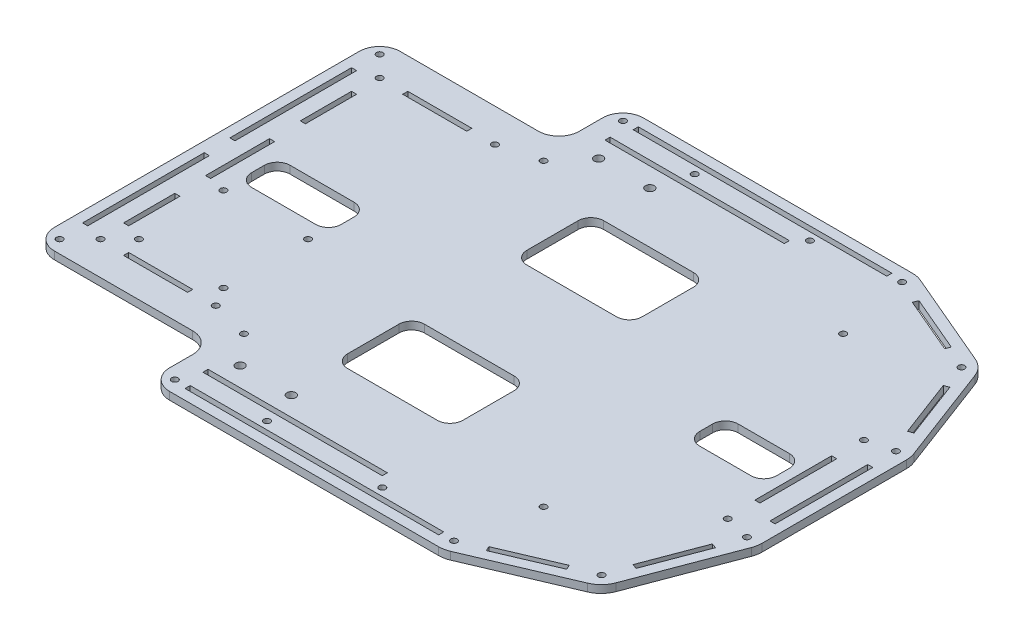
SolidWorks part; units mm, degrees
ref_plane "Piano frontale" through (0, 0, 0) normal (0, 0, 1) x (1, 0, 0)
ref_plane "Piano superiore" through (0, 0, 0) normal (0, 1, 0) x (1, 0, 0)
ref_plane "Piano destro" through (0, 0, 0) normal (1, 0, 0) x (0, 0, -1)
sketch "Schizzo1" plane through (0, 0, 0) normal (0, 1, 0) x (1, 0, 0)
  line L0 (70, 67.5) -> (70, 92.5)
  line L1 (0, 67.5) -> (70, 67.5)
  line L2 (0, 67.5) -> (0, -67.5)
  line L3 (0, -67.5) -> (70, -67.5)
  line L4 (70, 67.5) -> (70, -67.5) construction
  line L5 (70, 92.5) -> (185.0521, 92.5)
  line L6 (245, 30) -> (245, -30)
  line L7 (185.0521, -92.5) -> (70, -92.5)
  line L8 (70, -92.5) -> (70, -67.5)
  line L9 (245, 0) -> (70, 0) construction
  line L10 (245, 30) -> (228.3534, 74.0331)
  line L11 (228.3534, 74.0331) -> (185.0521, 92.5)
  line L12 (245, -30) -> (228.3534, -74.0331)
  line L13 (228.3534, -74.0331) -> (185.0521, -92.5)
  arc A0 (245, 30) -> (185.0521, 92.5) centre (185.0521, 32.5) ccw construction
  arc A1 (185.0521, -92.5) -> (245, -30) centre (185.0521, -32.5) ccw construction
  dimension "D5" = 60
  dimension "D6" = 60
  dimension "D1" = 135
  dimension "D2" = 70
  dimension "D3" = 175
  dimension "D4" = 25
extrude "Estrusione-Estrusione1" add sketch "Schizzo1" along normal blind 3
hole_wizard "Foro filettato M3x0.5-1" positions "Schizzo9" profile "Schizzo8" tap size "M3x0.5" standard "Ansi Metric"
sketch "Schizzo9" plane through (0, 3, 0) normal (0, 1, 0) x (1, 0, 0)
  line L102 (5, -62.5) -> (75, -62.5)
  line L103 (5, 62.5) -> (5, -62.5)
  line L104 (75, 62.5) -> (5, 62.5)
  line L105 (75, 87.5) -> (75, 62.5)
  line L106 (75, -62.5) -> (75, -87.5)
  line L107 (75, -87.5) -> (184.0304, -87.5)
  line L108 (184.0304, -87.5) -> (224.4305, -70.2704)
  line L109 (224.4305, -70.2704) -> (240, -29.0864)
  line L110 (240, -29.0864) -> (240, 29.0864)
  line L111 (240, 29.0864) -> (224.4305, 70.2704)
  line L112 (224.4305, 70.2704) -> (184.0304, 87.5)
  line L113 (184.0304, 87.5) -> (75, 87.5)
  line L114 (5, -62.5) -> (75, -62.5) construction
  line L115 (5, 62.5) -> (5, -62.5) construction
  line L116 (75, 62.5) -> (5, 62.5) construction
  line L117 (75, 87.5) -> (75, 62.5) construction
  line L118 (75, -62.5) -> (75, -87.5) construction
  line L119 (75, -87.5) -> (184.0304, -87.5) construction
  line L120 (184.0304, -87.5) -> (224.4305, -70.2704) construction
  line L121 (224.4305, -70.2704) -> (240, -29.0864) construction
  line L122 (240, -29.0864) -> (240, 29.0864) construction
  line L123 (240, 29.0864) -> (224.4305, 70.2704) construction
  line L124 (224.4305, 70.2704) -> (184.0304, 87.5) construction
  line L125 (184.0304, 87.5) -> (75, 87.5) construction
  point P0 (224.4305, 70.2704)
  point P2 (240, 29.0864)
  point P4 (240, -29.0864)
  point P6 (224.4305, -70.2704)
  point P8 (184.0304, -87.5)
  point P10 (184.0304, 87.5)
  point P12 (75, 87.5)
  point P14 (75, -87.5)
  point P16 (5, -62.5)
  point P18 (5, 62.5)
  dimension "D1" = 5
sketch "Schizzo8" plane through (224.4305, 3, -70.2704) normal (1, 0, 0) x (0, 0, 1)
  line L0 (0, 0) -> (0, 8.2511)
  line L1 (0, 8.2511) -> (1.25, 7.5)
  line L2 (1.25, 7.5) -> (1.25, 0)
  line L5 (1.25, 0) -> (0, 0)
  line L10 (0, 8.2511) -> (-1.25, 7.5) construction
  line L11 (0, -6.35) -> (0, 107.95) construction
  dimension "Tap Drill Dia." = 2.5
  dimension "Tap Drill Depth" = 7.5
  dimension "Drill Angle" = 118
cosmetic thread "Filettatura del foro1" parameters "D1"=5, "D2"=3
cosmetic thread "Filettatura del foro2" parameters "D1"=5, "D2"=3
cosmetic thread "Filettatura del foro3" parameters "D1"=5, "D2"=3
cosmetic thread "Filettatura del foro4" parameters "D1"=5, "D2"=3
cosmetic thread "Filettatura del foro5" parameters "D1"=5, "D2"=3
cosmetic thread "Filettatura del foro6" parameters "D1"=5, "D2"=3
cosmetic thread "Filettatura del foro7" parameters "D1"=5, "D2"=3
cosmetic thread "Filettatura del foro8" parameters "D1"=5, "D2"=3
cosmetic thread "Filettatura del foro9" parameters "D1"=5, "D2"=3
cosmetic thread "Filettatura del foro10" parameters "D1"=5, "D2"=3
sketch "Schizzo26" plane through (0, 3, 0) normal (0, 1, 0) x (1, 0, 0)
  line L0 (0, -67.5) -> (70, -67.5) construction
  line L1 (20, -67.5) -> (50, -67.5)
  line L2 (20, -67.5) -> (20, -64.5)
  line L3 (20, -64.5) -> (50, -64.5)
  line L4 (50, -67.5) -> (50, -64.5)
  line L6 (50, -66) -> (70, -66) construction
  line L7 (70, -66) -> (70, -67.5) construction
  line L8 (20, -66) -> (0, -66) construction
  line L10 (0, 67.5) -> (0, -67.5) construction
  dimension "D1" = 30
  dimension "D2" = 3
extrude "Taglio-Estrusione12" [suppressed] cut sketch "Schizzo26" against normal blind 10
mirror "Specchia1" [suppressed] about plane through (0, 0, 0) normal (0, 0, 1)
sketch "Schizzo4" plane through (0, 3, 0) normal (0, 1, 0) x (1, 0, 0)
  line L0 (127.5261, -92.5) -> (127.5261, -88.5) construction
  line L1 (85, -88.5) -> (174.0304, -88.5)
  line L2 (85, -88.5) -> (85, -86.5)
  line L3 (85, -86.5) -> (174.0304, -86.5)
  line L4 (174.0304, -88.5) -> (174.0304, -86.5)
  line L5 (235.5284, 38.0867) -> (227.0313, 60.5629)
  line L6 (174.0304, -87.5) -> (184.0304, -87.5) construction
  line L7 (184.0304, -87.5) -> (193.2289, -83.5771) construction
  line L8 (193.2289, -83.5771) -> (215.2321, -74.1933) construction
  line L9 (85, 88.5) -> (174.0304, 88.5)
  line L10 (85, 88.5) -> (85, 86.5)
  line L11 (85, 86.5) -> (174.0304, 86.5)
  line L12 (174.0304, 88.5) -> (174.0304, 86.5)
  line L13 (70, -92.5) -> (185.0521, -92.5) construction
  line L14 (85, -87.5) -> (75, -87.5) construction
  line L15 (227.0313, 60.5629) -> (228.9021, 61.2702)
  line L16 (127.5261, 92.5) -> (127.5261, 88.5) construction
  line L17 (185.0521, 92.5) -> (70, 92.5) construction
  line L18 (85, 87.5) -> (75, 87.5) construction
  line L19 (228.9021, 61.2702) -> (237.3992, 38.7939)
  line L20 (215.2321, -74.1933) -> (224.4305, -70.2704) construction
  line L21 (224.4305, -70.2704) -> (227.9667, -60.9165) construction
  line L22 (227.9667, -60.9165) -> (236.4638, -38.4403) construction
  line L23 (236.4638, -38.4403) -> (240, -29.0864) construction
  line L24 (240, -29.0864) -> (240, -19.0864) construction
  line L25 (240, -19.0864) -> (240, 19.0864) construction
  line L26 (240, 19.0864) -> (240, 29.0864) construction
  line L27 (240, 29.0864) -> (236.4638, 38.4403) construction
  line L28 (236.4638, 38.4403) -> (227.9667, 60.9165) construction
  line L29 (227.9667, 60.9165) -> (224.4305, 70.2704) construction
  line L30 (224.4305, 70.2704) -> (215.2321, 74.1933) construction
  line L31 (215.2321, 74.1933) -> (193.2289, 83.5771) construction
  line L32 (193.2289, 83.5771) -> (184.0304, 87.5) construction
  line L33 (184.0304, 87.5) -> (174.0304, 87.5) construction
  line L34 (215.6244, 75.1131) -> (193.6211, 84.497)
  line L35 (193.6211, 84.497) -> (192.8366, 82.6573)
  line L36 (192.8366, 82.6573) -> (214.8398, 73.2735)
  line L37 (214.8398, 73.2735) -> (215.6244, 75.1131)
  line L38 (228.3534, 74.0331) -> (185.0521, 92.5) construction
  line L39 (237.3992, 38.7939) -> (235.5284, 38.0867)
  line L40 (192.8366, -82.6573) -> (214.8398, -73.2735)
  line L41 (214.8398, -73.2735) -> (215.6244, -75.1131)
  line L42 (215.6244, -75.1131) -> (193.6211, -84.497)
  line L43 (193.6211, -84.497) -> (192.8366, -82.6573)
  line L44 (227.0313, -60.5629) -> (235.5284, -38.0867)
  line L45 (235.5284, -38.0867) -> (237.3992, -38.7939)
  line L46 (237.3992, -38.7939) -> (228.9021, -61.2702)
  line L47 (228.9021, -61.2702) -> (227.0313, -60.5629)
  dimension "D1" = 10
  dimension "D2" = 2
extrude "Taglio-Estrusione2" cut sketch "Schizzo4" against normal blind 10
hole_wizard "Foro filettato M3x0.5-7" positions "Schizzo31" profile "Schizzo30" tap size "M3x0.5" standard "Ansi Metric" end condition through all
sketch "Schizzo31" plane through (0, 3, 0) normal (0, 1, 0) x (1, 0, 0)
  line L0 (85, -86.5) -> (85, -83.5) construction
  line L1 (85, -83.5) -> (107.0152, -83.5) construction
  line L2 (107.0152, -83.5) -> (152.0152, -83.5) construction
  line L3 (152.0152, -83.5) -> (174.0304, -83.5) construction
  line L4 (174.0304, -83.5) -> (174.0304, -86.5) construction
  point P0 (107.0152, -83.5)
  point P2 (152.0152, -83.5)
  dimension "D1" = 45
  dimension "D2" = 3
sketch "Schizzo30" plane through (107.0152, 3, 83.5) normal (1, 0, 0) x (0, 0, 1)
  line L0 (0, 0) -> (0, 3)
  line L1 (0, 3) -> (1.25, 3)
  line L2 (1.25, 3) -> (1.25, 0)
  line L5 (1.25, 0) -> (0, 0)
  line L11 (0, -6.35) -> (0, 107.95) construction
  dimension "Thru Tap Drill Dia." = 2.5
  dimension "Thru Tap Drill Depth" = 3
cosmetic thread "Filettatura del foro27" parameters "D2"=3
cosmetic thread "Filettatura del foro28" parameters "D2"=3
sketch "Schizzo29" plane through (0, 3, 0) normal (0, 1, 0) x (1, 0, 0)
  line L0 (85, -88.5) -> (174.0304, -88.5) construction
  line L1 (85, -86.5) -> (80, -86.5)
  line L2 (85, -86.5) -> (85, -88.5)
  line L3 (85, -88.5) -> (80, -88.5)
  line L4 (80, -86.5) -> (80, -88.5)
  line L5 (174.0304, -86.5) -> (179.0304, -86.5)
  line L6 (174.0304, -86.5) -> (174.0304, -88.5)
  line L7 (174.0304, -88.5) -> (179.0304, -88.5)
  line L8 (179.0304, -86.5) -> (179.0304, -88.5)
  dimension "D1" = 5
extrude "Taglio-Estrusione13" cut sketch "Schizzo29" against normal blind 10
mirror "Specchia2" about plane through (0, 0, 0) normal (0, 0, 1) of "Foro filettato M3x0.5-7", "Taglio-Estrusione13"
sketch "Schizzo7" plane through (0, 3, 0) normal (0, 1, 0) x (1, 0, 0)
  line L0 (5, -52.5) -> (5, -62.5) construction
  line L1 (4, 52.5) -> (6, 52.5)
  line L2 (4, 52.5) -> (4, 5)
  line L3 (4, 5) -> (6, 5)
  line L4 (6, 52.5) -> (6, 5)
  line L5 (6, -5) -> (4, -5)
  line L6 (6, -5) -> (6, -52.5)
  line L7 (6, -52.5) -> (4, -52.5)
  line L8 (4, -5) -> (4, -52.5)
  line L9 (227.0313, -60.5629) -> (228.9021, -61.2702) construction
  line L10 (5, 52.5) -> (5, 62.5) construction
  line L12 (5, -5) -> (5, 5) construction
  line L13 (5, 0) -> (0, 0) construction
  line L14 (0, 67.5) -> (0, -67.5) construction
  line L16 (85, -87.5) -> (75, -87.5) construction
  line L19 (4, -28.75) -> (0, -28.75) construction
  dimension "D2" = 10
extrude "Taglio-Estrusione5" cut sketch "Schizzo7" against normal blind 10
sketch "Schizzo12" [suppressed] plane through (0, 6, 0) normal (0, 1, 0) x (1, 0, 0)
  line L0 (129.5152, 86.5) -> (129.5152, -86.5) construction
  line L1 (82, 20) -> (85, 20)
  line L2 (82, 20) -> (82, -20)
  line L3 (82, -20) -> (85, -20)
  line L4 (85, 20) -> (85, -20)
  line L5 (129.5152, 0) -> (140, 0) construction
  line L6 (140, 20) -> (143, 20)
  line L7 (140, 20) -> (140, -20)
  line L8 (140, -20) -> (143, -20)
  line L9 (85, 86.5) -> (174.0304, 86.5) construction
  line L10 (174.0304, -86.5) -> (85, -86.5) construction
  line L11 (85, 0) -> (129.5152, 0) construction
  line L12 (143, 20) -> (143, -20)
  line L13 (85, -86.5) -> (85, -20) construction
  dimension "D1" = 40
  dimension "D2" = 3
  dimension "D3" = 55
extrude "Taglio-Estrusione8" [suppressed] cut sketch "Schizzo12" against normal through all
sketch "Schizzo2" plane through (0, 3, 0) normal (0, 1, 0) x (1, 0, 0)
  line L0 (245, 20) -> (210, 20)
  line L1 (245, -30) -> (245, 30) construction
  line L2 (210, 20) -> (210, -20)
  line L3 (210, -20) -> (245, -20)
  line L4 (210, 0) -> (245, 0) construction
  line L5 (245, -30) -> (245, -20) construction
  line L6 (245, 30) -> (245, 20) construction
  line L7 (245, -30) -> (245, 30) construction
  dimension "D1" = 35
  dimension "D2" = 40
extrude "Taglio-Estrusione1" [suppressed] cut sketch "Schizzo2" against normal through all and the other way through all
sketch "Schizzo33" [suppressed] plane through (0, 6, 0) normal (0, 1, 0) x (1, 0, 0)
  line L0 (210, 20) -> (245, 20) construction
  line L1 (235.5, 20) -> (245, 20)
  line L2 (235.5, 20) -> (235.5, 23)
  line L3 (235.5, 23) -> (245, 23)
  line L4 (245, 20) -> (245, 23)
  line L5 (245, 20) -> (245, 30) construction
  dimension "D1" = 3
  dimension "D2" = 9.5
extrude "Taglio-Estrusione14" [suppressed] cut sketch "Schizzo33" against normal through all
mirror "Specchia3" [suppressed] about plane through (0, 0, 0) normal (0, 0, 1)
sketch "Schizzo11" [suppressed] plane through (0, 6, 0) normal (0, 1, 0) x (1, 0, 0)
  line L0 (235.5, -20) -> (210, -20) construction
  line L1 (239, -19.0864) -> (241, -19.0864)
  line L2 (239, -19.0864) -> (239, -20)
  line L3 (239, -20) -> (241, -20)
  line L4 (241, -19.0864) -> (241, -20)
  line L5 (210, 20) -> (235.5, 20) construction
  line L6 (239, 20) -> (241, 20)
  line L7 (239, 20) -> (239, 19.0864)
  line L8 (239, 19.0864) -> (241, 19.0864)
  line L9 (241, 20) -> (241, 19.0864)
  line L10 (237.3992, 38.7939) -> (235.5284, 38.0867) construction
  line L11 (235.5284, -38.0867) -> (237.3992, -38.7939) construction
extrude "Taglio-Estrusione7" [suppressed] cut sketch "Schizzo11" against normal blind 5
sketch "Schizzo10" plane through (0, 3, 0) normal (0, 1, 0) x (1, 0, 0)
  line L0 (237.3992, 38.7939) -> (235.5284, 38.0867) construction
  line L1 (239, -19.0864) -> (241, -19.0864)
  line L2 (239, -19.0864) -> (239, 19.0864)
  line L3 (239, 19.0864) -> (241, 19.0864)
  line L4 (241, -19.0864) -> (241, 19.0864)
extrude "Taglio-Estrusione6" cut sketch "Schizzo10" against normal through all
hole_wizard "Foro filettato M3x0.5-2" positions "Schizzo16" profile "Schizzo15" tap size "M3x0.5" standard "Ansi Metric" end condition through all
sketch "Schizzo16" plane through (0, 3, 0) normal (0, 1, 0) x (1, 0, 0)
  line L0 (13, 54.5) -> (58, 54.5) construction
  line L1 (58, 54.5) -> (58, -54.5) construction
  line L2 (58, -54.5) -> (13, -54.5) construction
  line L3 (13, -54.5) -> (13, 54.5) construction
  line L5 (0, 0) -> (13, 0) construction
  line L6 (0, 67.5) -> (0, -67.5) construction
  circle A0 centre (13, -54.5) radius 1.25 construction
  circle A1 centre (58, -54.5) radius 1.25 construction
  point P0 (13, 54.5)
  point P2 (13, -54.5)
  point P4 (58, -54.5)
  point P6 (58, 54.5)
sketch "Schizzo15" plane through (13, 3, -54.5) normal (1, 0, 0) x (0, 0, 1)
  line L0 (0, 0) -> (0, 3)
  line L1 (0, 3) -> (1.25, 3)
  line L2 (1.25, 3) -> (1.25, 0)
  line L5 (1.25, 0) -> (0, 0)
  line L11 (0, -6.35) -> (0, 107.95) construction
  dimension "Thru Tap Drill Dia." = 2.5
  dimension "Thru Tap Drill Depth" = 3
cosmetic thread "Filettatura del foro11" parameters "D2"=3
cosmetic thread "Filettatura del foro12" parameters "D2"=3
cosmetic thread "Filettatura del foro13" parameters "D2"=3
cosmetic thread "Filettatura del foro14" parameters "D2"=3
sketch "Schizzo17" plane through (0, 3, 0) normal (0, 1, 0) x (1, 0, 0)
  line L0 (58, -54.5) -> (48, -54.5) construction
  line L1 (48, -54.5) -> (23, -54.5) construction
  line L2 (23, -54.5) -> (13, -54.5) construction
  line L3 (13, -54.5) -> (13, -44.5) construction
  line L4 (13, -44.5) -> (13, 44.5) construction
  line L5 (13, 44.5) -> (13, 54.5) construction
  line L6 (13, 54.5) -> (23, 54.5) construction
  line L7 (23, 54.5) -> (48, 54.5) construction
  line L8 (48, 54.5) -> (58, 54.5) construction
  line L9 (48, -55.5) -> (48, -53.5) construction
  line L10 (23, -53.5) -> (48, -53.5)
  line L11 (23, -53.5) -> (23, -55.5)
  line L12 (23, -55.5) -> (48, -55.5)
  line L13 (48, -53.5) -> (48, -55.5)
  line L14 (14, -44.5) -> (12, -44.5)
  line L15 (14, -44.5) -> (14, -24.5)
  line L16 (14, 44.5) -> (12, 44.5)
  line L17 (12, -44.5) -> (12, -24.5)
  line L18 (23, 55.5) -> (48, 55.5)
  line L19 (23, 55.5) -> (23, 53.5)
  line L20 (23, 53.5) -> (48, 53.5)
  line L21 (48, 55.5) -> (48, 53.5)
  line L22 (12, 24.5) -> (14, 24.5)
  line L23 (12, 12.5) -> (14, 12.5)
  line L24 (12, 24.5) -> (12, 44.5)
  line L25 (14, 24.5) -> (14, 44.5)
  line L26 (12, -24.5) -> (14, -24.5)
  line L27 (12, -12.5) -> (14, -12.5)
  line L28 (12, -12.5) -> (12, 12.5)
  line L29 (14, -12.5) -> (14, 12.5)
  line L30 (13, 0) -> (12, 0) construction
  dimension "D2" = 25
  dimension "D1" = 2
  dimension "D3" = 20
extrude "Taglio-Estrusione9" cut sketch "Schizzo17" against normal blind 10
sketch "Schizzo18" plane through (0, 3, 0) normal (0, 1, 0) x (1, 0, 0)
  line L0 (113, -77.5) -> (113, 0) construction
  line L1 (78, 79.5) -> (148, 79.5)
  line L2 (78, 79.5) -> (78, 77.5)
  line L3 (78, 77.5) -> (148, 77.5)
  line L4 (148, 79.5) -> (148, 77.5)
  line L5 (78, -77.5) -> (148, -77.5)
  line L6 (78, -77.5) -> (78, -79.5)
  line L7 (78, -79.5) -> (148, -79.5)
  line L8 (148, -77.5) -> (148, -79.5)
  line L9 (113, 0) -> (113, 77.5) construction
  line L10 (0, 0) -> (113, 0) construction
  line L11 (148, -77.5) -> (78, -77.5) construction
  line L12 (78, -77.5) -> (78, -79.5) construction
  line L13 (78, -79.5) -> (148, -79.5) construction
extrude "Taglio-Estrusione10" cut sketch "Schizzo18" against normal blind 10
hole_wizard "Foro filettato M3x0.5-3" positions "Schizzo20" profile "Schizzo19" tap size "M3x0.5" standard "Ansi Metric" end condition through all
sketch "Schizzo20" plane through (0, 3, 0) normal (0, 1, 0) x (1, 0, 0)
  line L0 (230, 26.5864) -> (230, 0) construction
  line L1 (230, 0) -> (230, -26.5864) construction
  line L5 (245, 0) -> (230, 0) construction
  line L6 (245, -30) -> (245, 30) construction
  point P0 (230, 26.5864)
  point P2 (230, -26.5864)
sketch "Schizzo19" plane through (230, 3, -26.5864) normal (1, 0, 0) x (0, 0, 1)
  line L0 (0, 0) -> (0, 3)
  line L1 (0, 3) -> (1.25, 3)
  line L2 (1.25, 3) -> (1.25, 0)
  line L5 (1.25, 0) -> (0, 0)
  line L11 (0, -6.35) -> (0, 107.95) construction
  dimension "Thru Tap Drill Dia." = 2.5
  dimension "Thru Tap Drill Depth" = 3
cosmetic thread "Filettatura del foro15" parameters "D2"=3
cosmetic thread "Filettatura del foro16" parameters "D2"=3
hole_wizard "Foro filettato M3x0.5-4" [suppressed] positions "Schizzo22" profile "Schizzo21" tap size "M3x0.5" standard "Ansi Metric"
sketch "Schizzo22" plane through (0, 6, 0) normal (0, 1, 0) x (1, 0, 0)
  line L0 (209, 27) -> (209, -27) construction
  line L1 (209, 0) -> (210, 0) construction
  line L2 (210, -20) -> (210, 20) construction
  point P0 (209, 27)
  point P2 (209, -27)
  dimension "D1" = 54
  dimension "D2" = 1
sketch "Schizzo21" plane through (209, 6, -27) normal (1, 0, 0) x (0, 0, 1)
  line L0 (0, 0) -> (0, 6)
  line L1 (0, 6) -> (1.25, 6)
  line L2 (1.25, 6) -> (1.25, 0)
  line L5 (1.25, 0) -> (0, 0)
  line L11 (0, -6.35) -> (0, 107.95) construction
  dimension "Thru Tap Drill Dia." = 2.5
  dimension "Thru Tap Drill Depth" = 6
cosmetic thread "Filettatura del foro17" [suppressed] parameters "D2"=3
cosmetic thread "Filettatura del foro18" [suppressed] parameters "D2"=3
hole_wizard "Foro filettato M3x0.5-5" [suppressed] positions "Schizzo24" profile "Schizzo23" tap size "M3x0.5" standard "Ansi Metric"
sketch "Schizzo24" plane through (0, 6, 0) normal (0, 1, 0) x (1, 0, 0)
  line L0 (143, 65.3) -> (196, 65.3) construction
  line L1 (196, 65.3) -> (196, -65.3) construction
  line L2 (196, -65.3) -> (143, -65.3) construction
  line L3 (143, -65.3) -> (143, 65.3) construction
  line L5 (196, 0) -> (0, 0) construction
  line L6 (0, 67.5) -> (0, -67.5) construction
  line L7 (143, -20) -> (143, 20) construction
  point P0 (143, 65.3)
  point P2 (196, 65.3)
  point P4 (196, -65.3)
  point P6 (143, -65.3)
  dimension "D1" = 53
  dimension "D2" = 130.6
sketch "Schizzo23" plane through (143, 6, -65.3) normal (1, 0, 0) x (0, 0, 1)
  line L0 (0, 0) -> (0, 6)
  line L1 (0, 6) -> (1.25, 6)
  line L2 (1.25, 6) -> (1.25, 0)
  line L5 (1.25, 0) -> (0, 0)
  line L11 (0, -6.35) -> (0, 107.95) construction
  dimension "Thru Tap Drill Dia." = 2.5
  dimension "Thru Tap Drill Depth" = 6
cosmetic thread "Filettatura del foro19" [suppressed] parameters "D2"=3
cosmetic thread "Filettatura del foro20" [suppressed] parameters "D2"=3
cosmetic thread "Filettatura del foro21" [suppressed] parameters "D2"=3
cosmetic thread "Filettatura del foro22" [suppressed] parameters "D2"=3
sketch "Schizzo25" plane through (0, 3, 0) normal (0, 1, 0) x (1, 0, 0)
  line L0 (229, -15) -> (231, -15) construction
  line L1 (229, 15) -> (231, 15)
  line L2 (229, 15) -> (229, -15)
  line L3 (229, -15) -> (231, -15)
  line L4 (231, 15) -> (231, -15)
  line L5 (231, -15) -> (229, -15) construction
  line L6 (231, 15) -> (231, -15) construction
  line L7 (229, 15) -> (231, 15) construction
extrude "Taglio-Estrusione11" cut sketch "Schizzo25" against normal blind 10
hole_wizard "Foro filettato M3x0.5-6" positions "Schizzo28" profile "Schizzo27" tap size "M3x0.5" standard "Ansi Metric" end condition through all
sketch "Schizzo28" plane through (0, 3, 0) normal (0, 1, 0) x (1, 0, 0)
  line L0 (73, -58.5) -> (190, -58.5) construction
  line L1 (190, -58.5) -> (190, 58.5) construction
  line L2 (190, 58.5) -> (73, 58.5) construction
  line L3 (73, 58.5) -> (73, -58.5) construction
  line L4 (73, -58.5) -> (190, 58.5) construction
  line L6 (73, 58.5) -> (190, -58.5) construction
  circle A0 centre (73, 58.5) radius 1.65 construction
  circle A1 centre (190, 58.5) radius 1.65 construction
  circle A2 centre (73, -58.5) radius 1.65 construction
  point P0 (73, 58.5)
  point P2 (190, 58.5)
  point P4 (190, -58.5)
  point P6 (73, -58.5)
sketch "Schizzo27" plane through (73, 3, -58.5) normal (1, 0, 0) x (0, 0, 1)
  line L0 (0, 0) -> (0, 3)
  line L1 (0, 3) -> (1.25, 3)
  line L2 (1.25, 3) -> (1.25, 0)
  line L5 (1.25, 0) -> (0, 0)
  line L11 (0, -6.35) -> (0, 107.95) construction
  dimension "Thru Tap Drill Dia." = 2.5
  dimension "Thru Tap Drill Depth" = 3
cosmetic thread "Filettatura del foro23" parameters "D2"=3
cosmetic thread "Filettatura del foro24" parameters "D2"=3
cosmetic thread "Filettatura del foro25" parameters "D2"=3
cosmetic thread "Filettatura del foro26" parameters "D2"=3
hole_wizard "Foro filettato M3x0.5-8" [suppressed] positions "Schizzo35" profile "Schizzo34" tap size "M3x0.5" standard "Ansi Metric"
sketch "Schizzo35" plane through (0, 6, 0) normal (0, 1, 0) x (1, 0, 0)
  line L1 (16.064, -60.388) -> (46.036, -60.388) construction
  line L5 (31.05, -60.388) -> (31.05, -67.5) construction
  line L6 (0, -67.5) -> (70, -67.5) construction
  line L8 (0, 67.5) -> (0, -67.5) construction
  point P0 (16.064, -60.388)
  point P2 (46.036, -60.388)
  dimension "D1" = 29.972
  dimension "D2" = 7.112
  dimension "D3" = 31.05
sketch "Schizzo34" plane through (16.064, 6, 60.388) normal (1, 0, 0) x (0, 0, 1)
  line L0 (0, 0) -> (0, 6)
  line L1 (0, 6) -> (1.25, 6)
  line L2 (1.25, 6) -> (1.25, 0)
  line L5 (1.25, 0) -> (0, 0)
  line L11 (0, -6.35) -> (0, 107.95) construction
  dimension "Thru Tap Drill Dia." = 2.5
  dimension "Thru Tap Drill Depth" = 6
cosmetic thread "Filettatura del foro29" [suppressed] parameters "D2"=3
cosmetic thread "Filettatura del foro30" [suppressed] parameters "D2"=3
mirror "Specchia4" [suppressed] about plane through (0, 0, 0) normal (0, 0, 1)
sketch "Schizzo36" plane through (0, 3, 0) normal (0, 1, 0) x (1, 0, 0)
  line L0 (225, 0) -> (245, 0) construction
  line L1 (195, 7.5) -> (225, 7.5)
  line L2 (195, 7.5) -> (195, -7.5)
  line L3 (195, -7.5) -> (225, -7.5)
  line L4 (225, 7.5) -> (225, -7.5)
  line L5 (245, -30) -> (245, 30) construction
  dimension "D1" = 30
  dimension "D2" = 15
  dimension "D3" = 20
extrude "Taglio-Estrusione15" cut sketch "Schizzo36" against normal blind 10
sketch "Schizzo37" plane through (0, 3, 0) normal (0, 1, 0) x (1, 0, 0)
  line L0 (0, 0) -> (20, 0) construction
  line L1 (20, 7.5) -> (55, 7.5)
  line L2 (20, 7.5) -> (20, -7.5)
  line L3 (20, -7.5) -> (55, -7.5)
  line L4 (55, 7.5) -> (55, -7.5)
  line L5 (0, 67.5) -> (0, -67.5) construction
  dimension "D1" = 15
  dimension "D2" = 35
  dimension "D3" = 20
extrude "Taglio-Estrusione16" cut sketch "Schizzo37" against normal blind 10
sketch "Schizzo38" plane through (0, 3, 0) normal (0, 1, 0) x (1, 0, 0)
  line L0 (122.5, 20) -> (122.5, -20) construction
  line L1 (100, 50) -> (145, 50)
  line L2 (100, 50) -> (100, 20)
  line L3 (100, 20) -> (145, 20)
  line L4 (145, 50) -> (145, 20)
  line L5 (100, -20) -> (145, -20)
  line L6 (100, -20) -> (100, -50)
  line L7 (100, -50) -> (145, -50)
  line L8 (145, -20) -> (145, -50)
  line L9 (122.5, 0) -> (0, 0) construction
  line L10 (0, 67.5) -> (0, -67.5) construction
  line L11 (122.5, 0) -> (245, 0) construction
  line L12 (245, -30) -> (245, 30) construction
  dimension "D1" = 30
  dimension "D2" = 45
  dimension "D3" = 40
extrude "Taglio-Estrusione17" cut sketch "Schizzo38" against normal blind 10
hole_wizard "Foro filettato M3x0.5-9" positions "Schizzo40" profile "Schizzo39" tap size "M3x0.5" standard "Ansi Metric" end condition through all
sketch "Schizzo40" plane through (0, 3, 0) normal (0, 1, 0) x (1, 0, 0)
  line L0 (20.49, -13.99) -> (53.51, -13.99) construction
  line L1 (53.51, -13.99) -> (53.51, -47.01) construction
  line L2 (53.51, -47.01) -> (20.49, -47.01) construction
  line L3 (20.49, -47.01) -> (20.49, -13.99) construction
  line L12 (37, -13.99) -> (37, -7.5) construction
  line L13 (20, -7.5) -> (55, -7.5) construction
  line L15 (37, -47.01) -> (37, -53.5) construction
  line L16 (48, -53.5) -> (23, -53.5) construction
  line L18 (20.49, -30.5) -> (14, -30.5) construction
  line L19 (14, -44.5) -> (14, -24.5) construction
  point P0 (20.49, -47.01)
  point P2 (53.51, -47.01)
  point P4 (53.51, -13.99)
  point P6 (20.49, -13.99)
  dimension "D1" = 33.02
sketch "Schizzo39" plane through (20.49, 3, 47.01) normal (1, 0, 0) x (0, 0, 1)
  line L0 (0, 0) -> (0, 3)
  line L1 (0, 3) -> (1.25, 3)
  line L2 (1.25, 3) -> (1.25, 0)
  line L5 (1.25, 0) -> (0, 0)
  line L11 (0, -6.35) -> (0, 107.95) construction
  dimension "Thru Tap Drill Dia." = 2.5
  dimension "Thru Tap Drill Depth" = 3
cosmetic thread "Filettatura del foro31" parameters "D2"=3
cosmetic thread "Filettatura del foro32" parameters "D2"=3
cosmetic thread "Filettatura del foro33" parameters "D2"=3
cosmetic thread "Filettatura del foro34" parameters "D2"=3
fillet "Raccordo1" radius 8 6 edges at (0, 1.5, 67.5) (0, 1.5, -67.5) (70, 1.5, -92.5) (70, 1.5, 92.5) (70, 1.5, 67.5) (70, 1.5, -67.5)
fillet "Raccordo2" radius 10 6 edges at (185.0521, 1.5, -92.5) (228.3534, 1.5, -74.0331) (245, 1.5, -30) (245, 1.5, 30) (228.3534, 1.5, 74.0331) (185.0521, 1.5, 92.5)
fillet "Raccordo3" radius 5 16 edges at (195, 1.5, -7.5) (195, 1.5, 7.5) (225, 1.5, -7.5) (225, 1.5, 7.5) (55, 1.5, 7.5) (20, 1.5, 7.5) (20, 1.5, -7.5) (55, 1.5, -7.5) (100, 1.5, 20) (145, 1.5, 20) (100, 1.5, 50) (145, 1.5, 50) (145, 1.5, -20) (100, 1.5, -20) (100, 1.5, -50) (145, 1.5, -50)
hole_wizard "Foro per Vite M3-1" positions "Schizzo42" profile "Schizzo41" hole size "M3" standard "Ansi Metric" end condition through all
sketch "Schizzo42" plane through (0, 3, 0) normal (0, 1, 0) x (1, 0, 0)
  line L0 (83, 70) -> (83, -70) construction
  line L1 (83, -70) -> (103, -70) construction
  line L2 (103, -70) -> (103, 70) construction
  line L3 (103, 70) -> (83, 70) construction
  line L4 (83, 70) -> (103, -70) construction
  line L6 (0, 0) -> (93, 0) construction
  line L7 (0, 59.5) -> (0, -59.5) construction
  circle A0 centre (83, -70) radius 1.7 construction
  circle A1 centre (103, 70) radius 1.7 construction
  point P0 (83, 70)
  point P2 (103, 70)
  point P4 (103, -70)
  point P6 (83, -70)
sketch "Schizzo41" plane through (83, 3, -70) normal (1, 0, 0) x (0, 0, 1)
  line L0 (0, 0) -> (0, 3)
  line L1 (0, 3) -> (1.7, 3)
  line L2 (1.7, 3) -> (1.7, 0)
  line L5 (1.7, 0) -> (0, 0)
  line L11 (0, -6.35) -> (0, 107.95) construction
  dimension "Thru Hole Dia." = 3.4
  dimension "Thru Hole Depth" = 3
